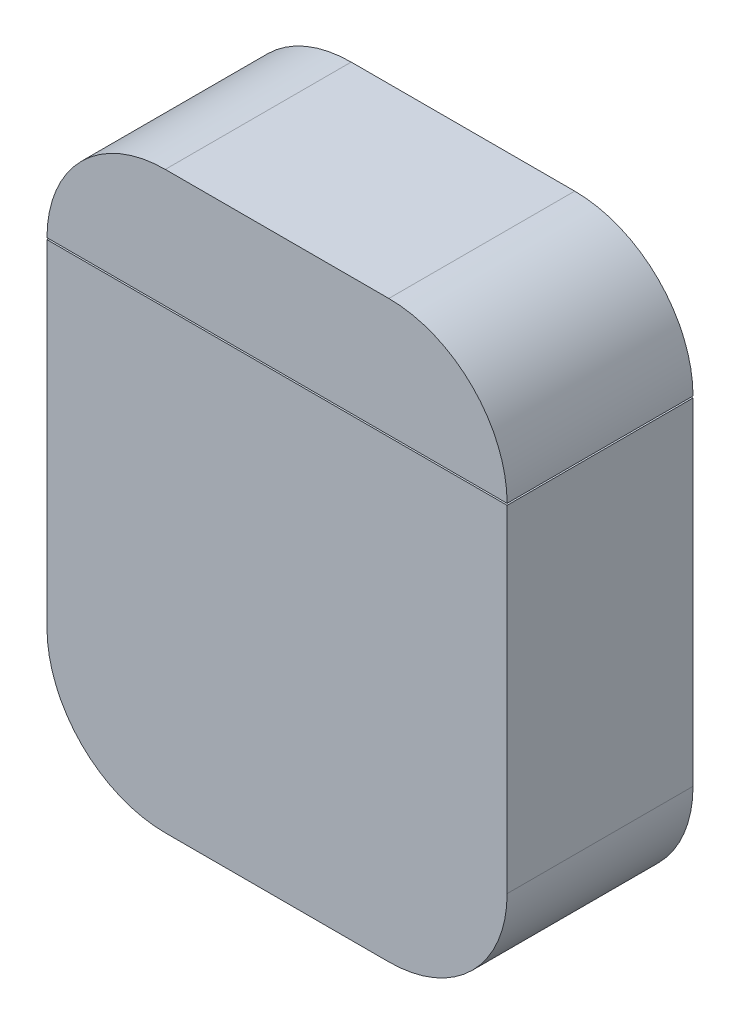
SolidWorks part; units mm, degrees
ref_plane "Front Plane" through (0, 0, 0) normal (0, 0, 1) x (1, 0, 0)
ref_plane "Top Plane" through (0, 0, 0) normal (0, 1, 0) x (1, 0, 0)
ref_plane "Right Plane" through (0, 0, 0) normal (1, 0, 0) x (0, 0, -1)
sketch "Sketch1" plane through (0, 0, 0) normal (0, 0, 1) x (1, 0, 0)
  line L0 (109.0306, 26.3438) -> (-58.9526, 26.3438)
  line L1 (-147.8526, -62.5562) -> (-147.8526, -316.5562)
  line L2 (-58.9526, -405.4562) -> (109.0306, -405.4562)
  line L3 (197.9306, -316.5562) -> (197.9306, -62.5562)
  arc A0 (-58.9526, 26.3438) -> (-147.8526, -62.5562) centre (-58.9526, -62.5562) ccw
  arc A1 (-147.8526, -316.5562) -> (-58.9526, -405.4562) centre (-58.9526, -316.5562) ccw
  arc A2 (109.0306, -405.4562) -> (197.9306, -316.5562) centre (109.0306, -316.5562) ccw
  arc A3 (197.9306, -62.5562) -> (109.0306, 26.3438) centre (109.0306, -62.5562) ccw
  dimension "D1" = 88.9
  dimension "D2" = 254
extrude "Boss-Extrude1" add sketch "Sketch1" along normal blind 139.7 contours A2 L3 A3 L0 A0 L1 A1 L2
sketch "Sketch2" plane through (0, 0, 139.7) normal (0, 0, 1) x (1, 0, 0)
  line L0 (197.9306, -316.5562) -> (197.9306, -62.5562) construction
  line L5 (-147.8526, -62.5562) -> (197.9306, -62.5562)
  line L6 (-147.8526, -62.5562) -> (-147.8526, -63.8262)
  line L7 (-147.8526, -63.8262) -> (197.9306, -63.8262)
  line L8 (197.9306, -62.5562) -> (197.9306, -63.8262)
  dimension "D1" = 1.27
extrude "Cut-Extrude1" cut sketch "Sketch2" against normal blind 5.08
sketch "Sketch3" plane through (-147.8526, 0, 0) normal (-1, 0, 0) x (0, 0, 1)
  line L0 (134.62, -62.5562) -> (0, -62.5562)
  line L1 (134.62, -62.5562) -> (134.62, -63.8262)
  line L2 (134.62, -63.8262) -> (0, -63.8262)
  line L3 (0, -62.5562) -> (0, -316.5562) construction
  line L4 (0, -63.8262) -> (0, -62.5562)
extrude "Cut-Extrude2" cut sketch "Sketch3" against normal blind 5.08
sketch "Sketch4" plane through (197.9306, 0, 0) normal (1, 0, 0) x (0, 0, -1)
  line L0 (-134.62, -62.5562) -> (-134.62, -63.8262)
  line L1 (-134.62, -63.8262) -> (0, -63.8262)
  line L2 (0, -316.5562) -> (0, -62.5562) construction
  line L3 (0, -63.8262) -> (0, -62.5562)
  line L4 (0, -62.5562) -> (-134.62, -62.5562)
extrude "Cut-Extrude3" cut sketch "Sketch4" against normal blind 5.08
sketch "Sketch5" plane through (0, 0, 0) normal (0, 0, -1) x (-1, 0, 0)
  line L0 (58.9526, -405.4562) -> (-109.0306, -405.4562) construction
  line L1 (-197.9306, -316.5562) -> (-197.9306, -63.8262) construction
  line L5 (-192.8506, -62.5562) -> (-116.6506, -62.5562)
  line L7 (142.7726, -62.5562) -> (66.5726, -62.5562)
  line L8 (-192.8506, -62.5562) -> (-192.8506, -63.8262)
  line L9 (-192.8506, -63.8262) -> (-116.6506, -63.8262)
  line L10 (-116.6506, -63.8262) -> (-116.6506, -62.5562)
  line L11 (142.7726, -62.5562) -> (142.7726, -63.8262)
  line L12 (142.7726, -63.8262) -> (66.5726, -63.8262)
  line L13 (66.5726, -63.8262) -> (66.5726, -62.5562)
  dimension "D1" = 76.2
extrude "Cut-Extrude4" cut sketch "Sketch5" against normal blind 5.08
sketch "Sketch7" plane through (0, 0, 0) normal (0, 0, -1) x (-1, 0, 0)
  line L6 (66.5726, -63.8262) -> (147.8526, -63.8262) construction
  line L7 (93.2172, -63.8262) -> (93.2172, -85.0174)
  line L9 (80.5172, -97.7174) -> (-130.3028, -97.7174)
  line L13 (-116.6506, -63.8262) -> (-197.9306, -63.8262) construction
  line L14 (-143.0028, -63.8262) -> (-143.0028, -85.0174)
  line L16 (93.2172, -62.5562) -> (93.2172, -63.8262)
  line L17 (66.5726, -62.5562) -> (147.8526, -62.5562) construction
  line L18 (93.2172, -62.5562) -> (-143.0028, -62.5562)
  line L19 (-116.6506, -62.5562) -> (-197.9306, -62.5562) construction
  line L20 (-143.0028, -62.5562) -> (-143.0028, -63.8262)
  line L21 (147.8526, -63.8262) -> (147.8526, -316.5562) construction
  arc A0 (-143.0028, -85.0174) -> (-130.3028, -97.7174) centre (-130.3028, -85.0174) ccw
  arc A1 (80.5172, -97.7174) -> (93.2172, -85.0174) centre (80.5172, -85.0174) ccw
  dimension "D1" = 12.7
  dimension "D2" = 210.82
  dimension "1.9" = 54.6354
extrude "Cut-Extrude-Thin1" cut sketch "Sketch7" against normal blind 2.54 thin thin type one direction wall 2.54
sketch "Sketch8" plane through (0, 0, 0) normal (0, 0, -1) x (-1, 0, 0)
  line L0 (-116.6506, -62.5562) -> (-116.6506, -97.7174)
  line L1 (-130.3028, -97.7174) -> (80.5172, -97.7174) construction
  line L2 (-116.6506, -97.7174) -> (-115.967, -97.7174)
  line L3 (-115.967, -97.7174) -> (-115.967, -62.5562)
  line L4 (66.5726, -62.5562) -> (-116.6506, -62.5562) construction
  line L5 (-115.967, -62.5562) -> (-116.6506, -62.5562)
  line L6 (66.5726, -62.5562) -> (66.5726, -97.7174)
  line L7 (66.5726, -97.7174) -> (65.7203, -97.7174)
  line L8 (-130.3028, -97.7174) -> (80.5172, -97.7174) construction
  line L9 (65.7203, -97.7174) -> (65.7203, -62.5562)
  line L10 (65.7203, -62.5562) -> (66.5726, -62.5562)
extrude "Cut-Extrude5" cut sketch "Sketch8" against normal blind 2.54
sketch "Sketch9" plane through (0, 0, 0) normal (0, 0, -1) x (-1, 0, 0)
  circle A0 centre (-24.8928, -221.5113) radius 24.8928
extrude "Cut-Extrude-Thin2" cut sketch "Sketch9" against normal blind 2.54 thin
